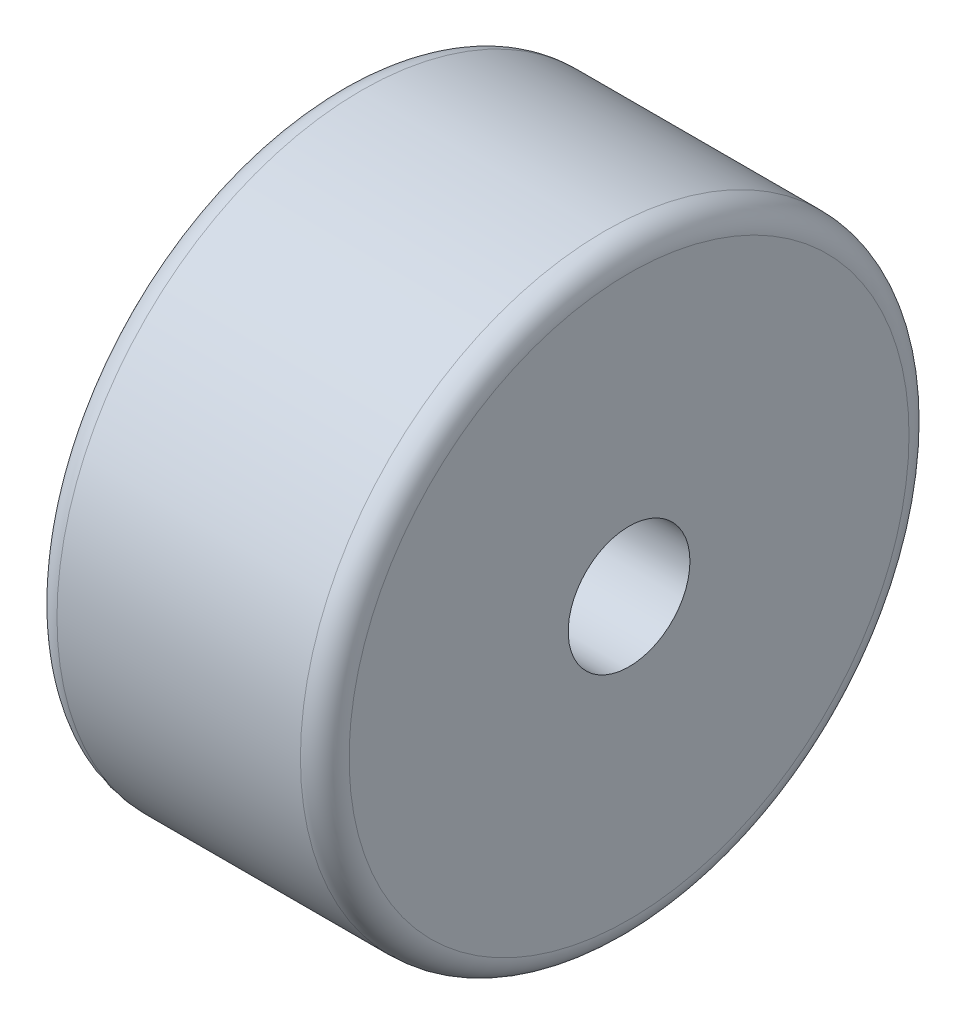
SolidWorks part; units mm, degrees
ref_plane "Plan de face" through (0, 0, 0) normal (0, 0, 1) x (1, 0, 0)
ref_plane "Plan de dessus" through (0, 0, 0) normal (0, 1, 0) x (1, 0, 0)
ref_plane "Plan de droite" through (0, 0, 0) normal (1, 0, 0) x (0, 0, -1)
sketch "Esquisse1" plane through (0, 0, 0) normal (1, 0, 0) x (0, 0, -1)
  circle A0 centre (0, 0) radius 12.5
  dimension "D1" = 25
extrude "Boss.-Extru.1" add sketch "Esquisse1" along normal blind 12
sketch "Esquisse2" plane through (12, 0, 0) normal (1, 0, 0) x (0, 0, -1)
  circle A0 centre (0, 0) radius 2.5
  dimension "D1" = 5
extrude "Enlèv. mat.-Extru.1" cut sketch "Esquisse2" against normal blind 12
fillet "Congé1" radius 1 2 edges at (12, 0, -12.5) (0, 0, -12.5)
